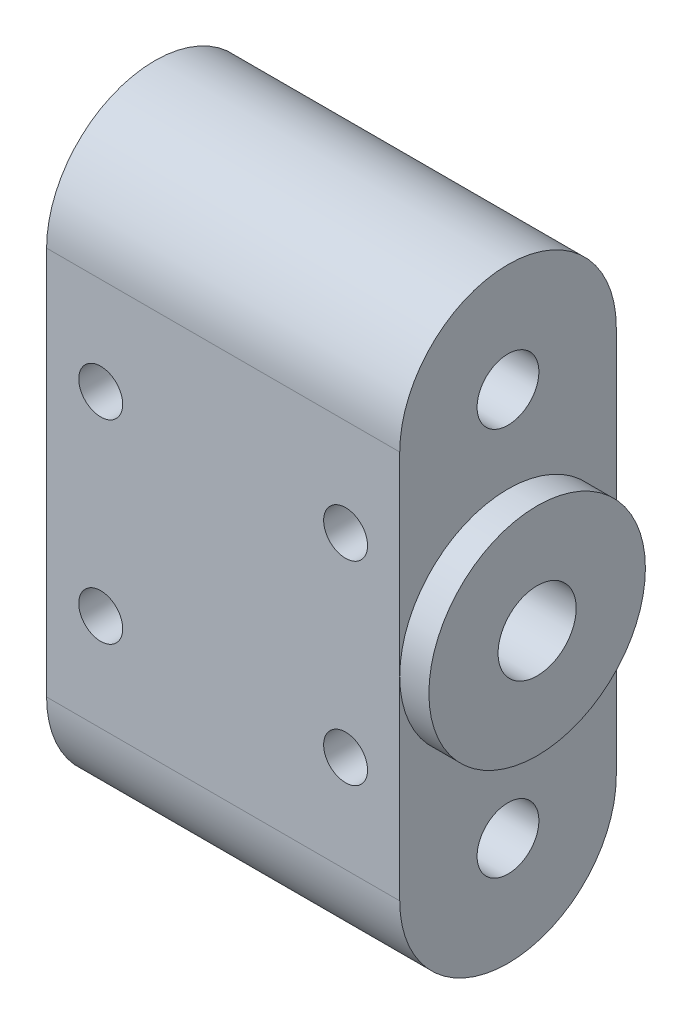
SolidWorks part; units mm, degrees
material "PET"
ref_plane "Front" through (0, 0, 0) normal (0, 0, 1) x (1, 0, 0)
ref_plane "Top" through (0, 0, 0) normal (0, 1, 0) x (1, 0, 0)
ref_plane "Right" through (0, 0, 0) normal (1, 0, 0) x (0, 0, -1)
sketch "Sketch1" plane through (0, 0, 0) normal (1, 0, 0) x (0, 0, -1)
  line L0 (0, 12.7) -> (0, -12.7) construction
  line L1 (7.0739, 12.7) -> (7.0739, -12.7)
  line L2 (-7.0739, 12.7) -> (-7.0739, -12.7)
  arc A0 (7.0739, 12.7) -> (-7.0739, 12.7) centre (0, 12.7) ccw
  arc A1 (-7.0739, -12.7) -> (7.0739, -12.7) centre (0, -12.7) ccw
  point P2 (0, 0)
  dimension "D1" = 14.1478
  dimension "D2" = 25.4
extrude "Boss-Extrude1" add sketch "Sketch1" along normal blind 23.075
sketch "Sketch8" plane through (23.075, 0, 0) normal (1, 0, 0) x (0, 0, -1)
  circle A0 centre (0, 0) radius 7.0739
  dimension "D1" = 14.1478
extrude "Boss-Extrude2" add sketch "Sketch8" along normal blind 1.905
hole_wizard "1/4-20 Tapped Hole1" positions "Sketch9" profile "Sketch10" tap size "1/4-20" standard "ANSI Inch" end condition through all
sketch "Sketch9" plane through (24.98, 0, 0) normal (1, 0, 0) x (0, 0, -1)
  point P0 (0, 0)
sketch "Sketch10" plane through (24.98, 0, 0) normal (0, 1, 0) x (0, 0, -1)
  line L0 (0, 0) -> (0, 24.98)
  line L1 (0, 24.98) -> (2.5527, 24.98)
  line L2 (2.5527, 24.98) -> (2.5527, 0)
  line L5 (2.5527, 0) -> (0, 0)
  line L11 (0, -6.35) -> (0, 107.95) construction
  dimension "Thru Tap Drill Dia." = 5.1054
  dimension "Thru Tap Drill Depth" = 24.98
cosmetic thread "Hole Thread8" parameters "D2"=6.35
hole_wizard "#10-32 Tapped Hole1" positions "Sketch4" profile "Sketch5" tap size "#10-32" standard "ANSI Inch" end condition through all
sketch "Sketch4" plane through (23.075, 0, 0) normal (1, 0, 0) x (0, 0, -1)
  point P0 (0, 12.7)
  point P2 (0, -12.7)
sketch "Sketch5" plane through (23.075, 12.7, 0) normal (0, 1, 0) x (0, 0, -1)
  line L0 (0, 0) -> (0, 23.075)
  line L1 (0, 23.075) -> (2.0193, 23.075)
  line L2 (2.0193, 23.075) -> (2.0193, 0)
  line L5 (2.0193, 0) -> (0, 0)
  line L11 (0, -6.35) -> (0, 107.95) construction
  dimension "Thru Tap Drill Dia." = 4.0386
  dimension "Thru Tap Drill Depth" = 23.075
cosmetic thread "Hole Thread2" parameters "D2"=4.826
cosmetic thread "Hole Thread3" parameters "D2"=4.826
hole_wizard "#6-40 Tapped Hole1" positions "Sketch6" profile "Sketch7" tap size "#6-40" standard "ANSI Inch" end condition through all
sketch "Sketch6" plane through (0, 0, 7.0739) normal (0, 0, 1) x (1, 0, 0)
  line L5 (3.5375, 6.35) -> (3.5375, -6.35) construction
  line L7 (0, 0) -> (23.075, 0) construction
  line L8 (0, 12.7) -> (0, -12.7) construction
  line L12 (3.5375, 6.35) -> (19.5375, 6.35) construction
  line L14 (11.5375, 6.35) -> (11.5375, 0) construction
  line L15 (23.075, 12.7) -> (23.075, 0) construction
  point P0 (3.5375, 6.35)
  point P2 (19.5375, 6.35)
  point P4 (3.5375, -6.35)
  point P6 (19.5375, -6.35)
  point P54 (3.5375, 0)
  dimension "D1" = 16
  dimension "D2" = 12.7
cosmetic thread "Hole Thread4" parameters "D2"=3.5052
cosmetic thread "Hole Thread5" parameters "D2"=3.5052
cosmetic thread "Hole Thread6" parameters "D2"=3.5052
cosmetic thread "Hole Thread7" parameters "D2"=3.5052
sketch "Sketch7" plane through (3.5375, 6.35, 7.0739) normal (1, 0, 0) x (0, -1, 0)
  line L0 (0, 0) -> (0, 14.1478)
  line L1 (0, 14.1478) -> (1.4351, 14.1478)
  line L2 (1.4351, 14.1478) -> (1.4351, 0)
  line L5 (1.4351, 0) -> (0, 0)
  line L11 (0, -6.35) -> (0, 107.95) construction
  dimension "Thru Tap Drill Dia." = 2.8702
  dimension "Thru Tap Drill Depth" = 14.1478
hole_wizard "13/64 (0.20313) Diameter Hole1" positions "Sketch11" profile "Sketch12" hole size "13/64" standard "ANSI Inch"
sketch "Sketch11" plane through (0, 0, 0) normal (-1, 0, 0) x (0, 0, 1)
  point P0 (0, -12.7)
  point P3 (0, 12.7)
sketch "Sketch12" plane through (0, -12.7, 0) normal (0, 1, 0) x (0, 0, 1)
  line L0 (0, 0) -> (0, 4.7251)
  line L1 (0, 4.7251) -> (2.5798, 3.175)
  line L2 (2.5798, 3.175) -> (2.5798, 0)
  line L5 (2.5798, 0) -> (0, 0)
  line L10 (0, 4.7251) -> (-2.5798, 3.175) construction
  line L11 (0, -6.35) -> (0, 107.95) construction
  dimension "Hole Dia." = 5.1595
  dimension "Hole Depth" = 3.175
  dimension "Drill Angle" = 118
